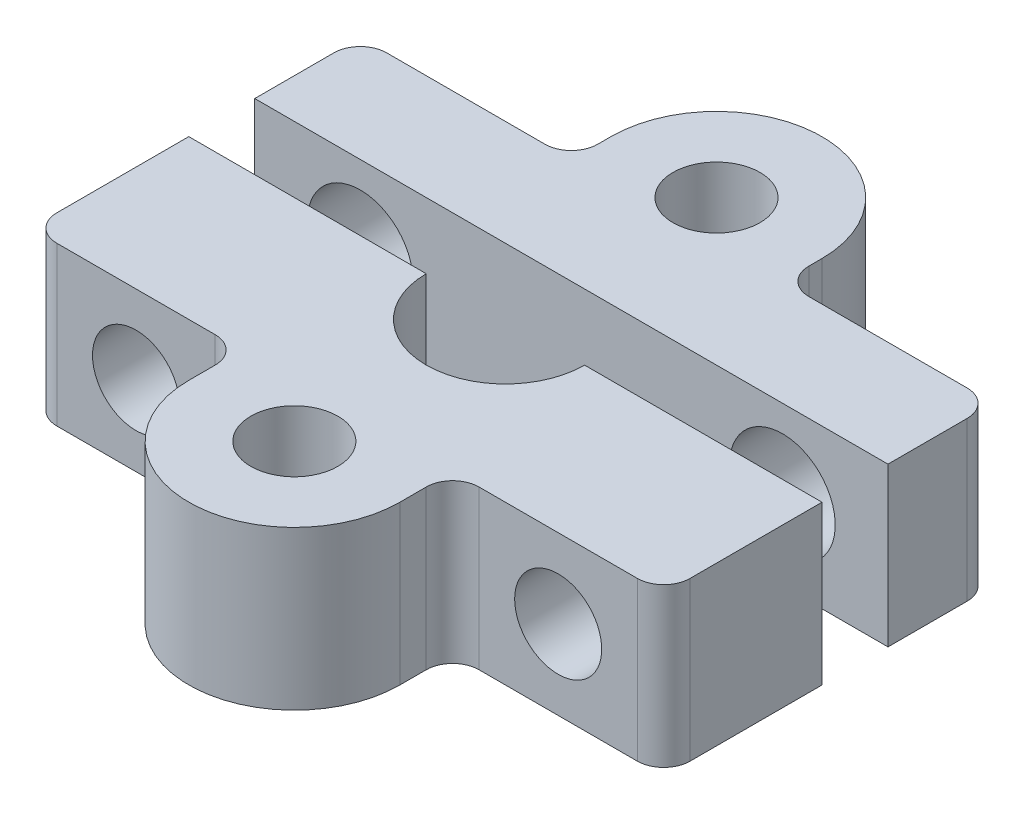
SolidWorks part; units mm, degrees
ref_plane "前视基准面" through (0, 0, 0) normal (0, 0, 1) x (1, 0, 0)
ref_plane "上视基准面" through (0, 0, 0) normal (0, 1, 0) x (1, 0, 0)
ref_plane "右视基准面" through (0, 0, 0) normal (1, 0, 0) x (0, 0, -1)
sketch "草图1" plane through (0, 0, 0) normal (0, 1, 0) x (1, 0, 0)
  line L1 (-3, 0) -> (-12, 0)
  line L2 (-12, 0) -> (-12, -5)
  line L3 (-11, -6) -> (-5, -6)
  line L4 (12, -5) -> (12, 0)
  line L5 (12, 0) -> (3, 0)
  line L6 (0, 0) -> (0, -6.7259) construction
  line L7 (12, 2.5) -> (-12, 2.5)
  line L8 (-12, 2.5) -> (-12, 5.5)
  line L9 (-11, 6.5) -> (-5, 6.5)
  line L10 (12, 5.5) -> (12, 2.5)
  line L11 (-4, -8) -> (-4, -7)
  line L12 (4, -8) -> (4, -7)
  line L13 (5, -6) -> (11, -6)
  line L14 (0, 0) -> (15.0315, 0) construction
  line L15 (-4, 8) -> (-4, 7.5)
  line L16 (4, 8) -> (4, 7.5)
  line L17 (5, 6.5) -> (11, 6.5)
  arc A0 (-3, 0) -> (3, 0) centre (0, 0) ccw
  arc A1 (11, -6) -> (12, -5) centre (11, -5) ccw
  arc A2 (-12, -5) -> (-11, -6) centre (-11, -5) ccw
  arc A3 (-4, -8) -> (4, -8) centre (0, -8) ccw
  arc A4 (4, -7) -> (5, -6) centre (5, -7) cw
  arc A5 (-4, -7) -> (-5, -6) centre (-5, -7) ccw
  arc A6 (4, 8) -> (-4, 8) centre (0, 8) ccw
  arc A7 (4, 7.5) -> (5, 6.5) centre (5, 7.5) ccw
  arc A8 (-4, 7.5) -> (-5, 6.5) centre (-5, 7.5) cw
  arc A9 (11, 6.5) -> (12, 5.5) centre (11, 5.5) cw
  arc A10 (-12, 5.5) -> (-11, 6.5) centre (-11, 5.5) cw
  point P13 (-12, -6)
  point P25 (4, -6)
  point P36 (4, 6.5)
  point P41 (12, 6.5)
  dimension "D2" = 3
  dimension "D4" = 1
  dimension "D8" = 8
  dimension "D9" = 1
  dimension "D10" = 1
  dimension "D11" = 1
  dimension "D1" = 6
  dimension "D3" = 12
  dimension "D5" = 2.5
  dimension "D6" = 4
  dimension "D7" = 8
extrude "凸台-拉伸1" add sketch "草图1" along normal blind 6
sketch "草图2" plane through (0, 0, 0) normal (0, 0, -1) x (-1, 0, 0)
  line L0 (-12, 3) -> (12, 3) construction
  line L1 (-12, 6) -> (-12, 0) construction
  line L2 (12, 6) -> (12, 0) construction
  line L3 (0, 0) -> (0, 6) construction
  line L4 (3, 6) -> (-3, 6) construction
  line L5 (-3, 6) -> (-3, 0) construction
  circle A0 centre (-8, 3) radius 1.65
  circle A1 centre (8, 3) radius 1.65
  dimension "D2" = 3.3
  dimension "D1" = 5
extrude "切除-拉伸2" cut sketch "草图2" against normal through all both and the other way through all
cosmetic thread "装饰螺纹线3" parameters "D2"=4
cosmetic thread "装饰螺纹线4" parameters "D2"=4
sketch "草图3" plane through (0, 0, 0) normal (0, -1, 0) x (1, 0, 0)
  line L0 (0, 0) -> (12.0569, 0) construction
  circle A0 centre (0, 8) radius 1.65
  circle A1 centre (0, -8) radius 1.65
  dimension "D1" = 3.3
  dimension "D2" = 8
extrude "切除-拉伸3" cut sketch "草图3" against normal blind 8
cosmetic thread "装饰螺纹线1" parameters "D2"=4
cosmetic thread "装饰螺纹线2" parameters "D2"=4
sketch "草图4" plane through (0, 0, -6.5) normal (0, 0, -1) x (-1, 0, 0)
  circle A0 centre (-8, 3) radius 2
  circle A1 centre (8, 3) radius 2
  dimension "D1" = 4
  dimension "D2" = 4
extrude "切除-拉伸4" cut sketch "草图4" against normal blind 5
